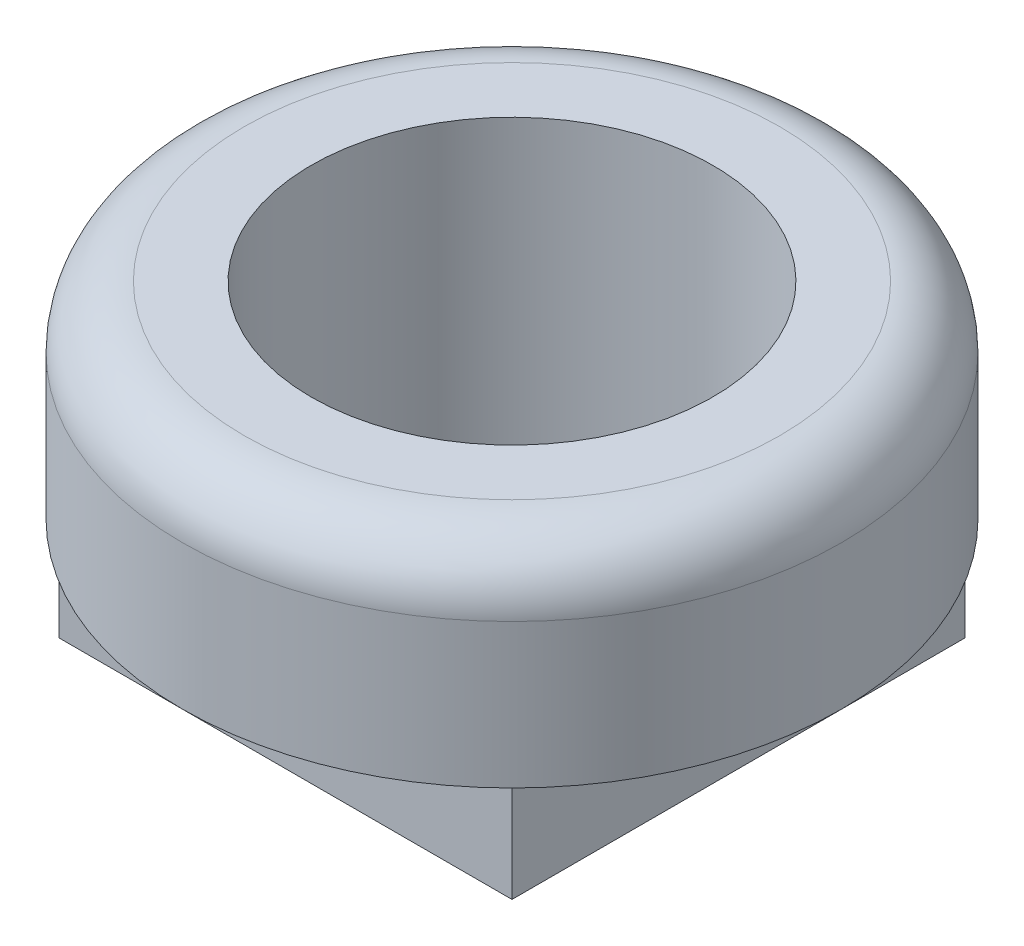
SolidWorks part; units mm, degrees
ref_plane "Front Plane" through (0, 0, 0) normal (0, 0, 1) x (1, 0, 0)
ref_plane "Top Plane" through (0, 0, 0) normal (0, 1, 0) x (1, 0, 0)
ref_plane "Right Plane" through (0, 0, 0) normal (1, 0, 0) x (0, 0, -1)
sketch "Sketch1" plane through (0, 0, 0) normal (0, 1, 0) x (1, 0, 0)
  circle A0 centre (0, 0) radius 16
  dimension "D1" = 32
extrude "Boss-Extrude1" add sketch "Sketch1" along normal blind 10
sketch "Sketch2" plane through (0, 0, 0) normal (0, -1, 0) x (1, 0, 0)
  line L1 (11, 11) -> (-11, 11)
  line L2 (11, 11) -> (11, -11)
  line L3 (11, -11) -> (-11, -11)
  line L4 (-11, 11) -> (-11, -11)
  line L5 (11, 11) -> (-11, -11) construction
  line L6 (11, -11) -> (-11, 11) construction
  point P0 (0, 0)
  dimension "D1" = 22
extrude "Boss-Extrude2" add sketch "Sketch2" along normal blind 5
sketch "Sketch3" plane through (0, 10, 0) normal (0, 1, 0) x (1, 0, 0)
  circle A0 centre (0, 0) radius 9.75
  dimension "D1" = 19.5
extrude "Cut-Extrude1" cut sketch "Sketch3" against normal through all
fillet "Fillet1" radius 3 1 edges at (0, 10, 16)
